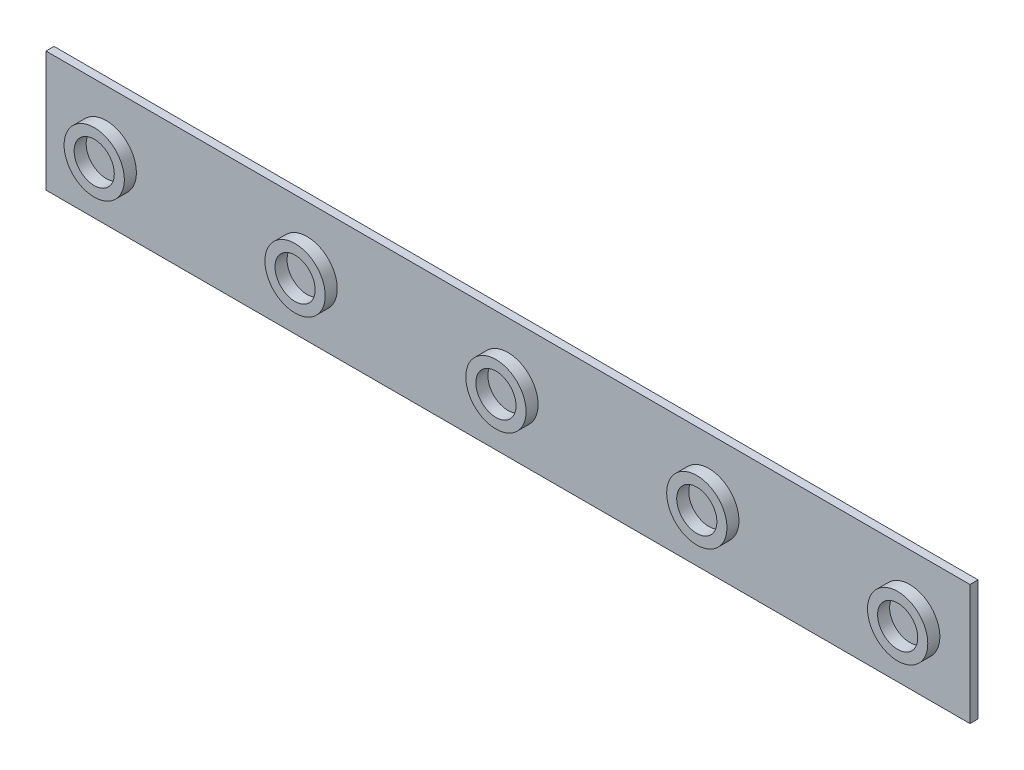
SolidWorks part; units mm, degrees
ref_plane "Plan de face" through (0, 0, 0) normal (0, 0, 1) x (1, 0, 0)
ref_plane "Plan de dessus" through (0, 0, 0) normal (0, 1, 0) x (1, 0, 0)
ref_plane "Plan de droite" through (0, 0, 0) normal (1, 0, 0) x (0, 0, -1)
sketch "Esquisse1" plane through (0, 0, 0) normal (0, 0, 1) x (1, 0, 0)
  line L1 (0, 0) -> (230, 0)
  line L2 (0, 0) -> (0, 30)
  line L3 (0, 30) -> (230, 30)
  line L4 (230, 0) -> (230, 30)
  circle A0 centre (15, 15) radius 7.5 construction
  circle A1 centre (65, 15) radius 7.5 construction
  circle A2 centre (115, 15) radius 7.5 construction
  circle A3 centre (165, 15) radius 7.5 construction
  circle A4 centre (215, 15) radius 7.5 construction
  dimension "D1" = 15
  dimension "D2" = 15
  dimension "D3" = 15
  dimension "D4" = 15
  dimension "D5" = 50
  dimension "D6" = 50
  dimension "D7" = 50
  dimension "D8" = 15
  dimension "D9" = 50
  dimension "D10" = 15
  dimension "D11" = 15
  dimension "D12" = 15
  dimension "D13" = 15
extrude "Boss.-Extru.1" add sketch "Esquisse1" along normal blind 2
sketch "Esquisse2" plane through (0, 0, 2) normal (0, 0, 1) x (1, 0, 0)
  circle A0 centre (15, 15) radius 7.5
  circle A1 centre (65, 15) radius 7.5
  circle A2 centre (115, 15) radius 7.5
  circle A3 centre (165, 15) radius 7.5
  circle A4 centre (215, 15) radius 7.5
  circle A5 centre (15, 15) radius 5
  circle A6 centre (65, 15) radius 5
  circle A7 centre (115, 15) radius 5
  circle A8 centre (165, 15) radius 5
  circle A9 centre (215, 15) radius 5
  dimension "D1" = 10
  dimension "D2" = 10
  dimension "D3" = 10
  dimension "D4" = 10
  dimension "D5" = 10
extrude "Boss.-Extru.2" add sketch "Esquisse2" along normal blind 3
